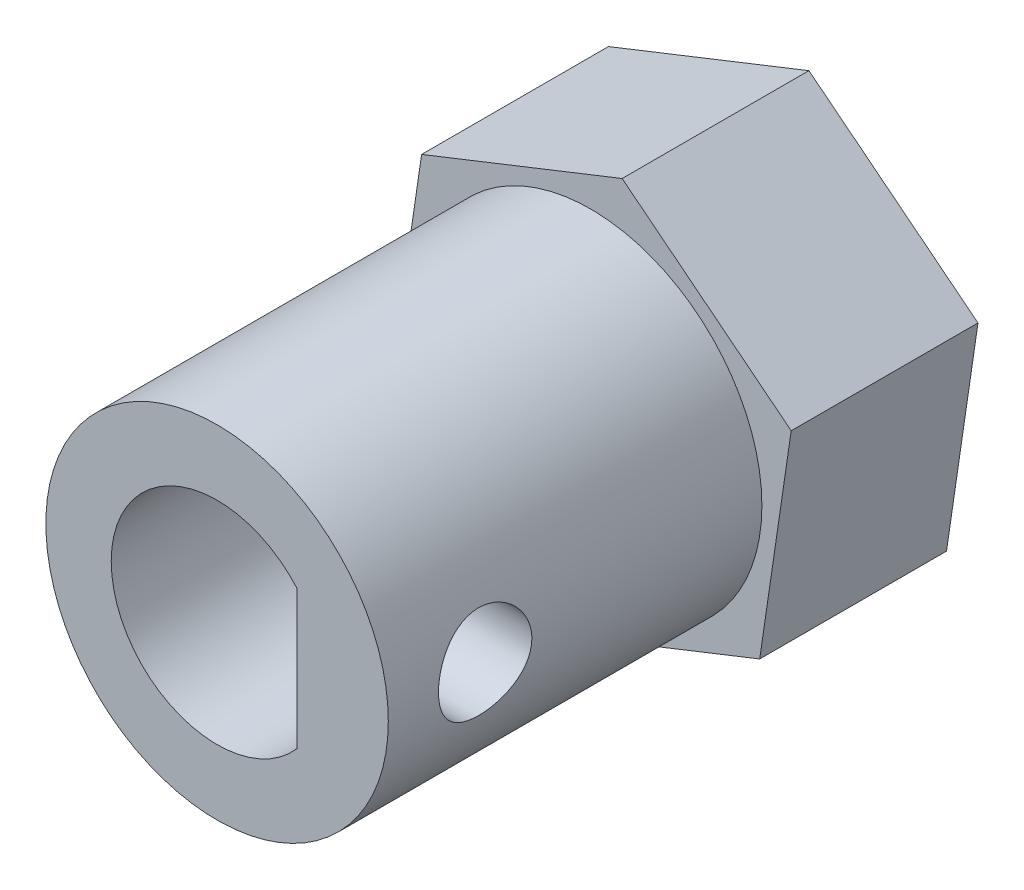
SolidWorks part; units mm, degrees
ref_plane "前视基准面" through (0, 0, 0) normal (0, 0, 1) x (1, 0, 0)
ref_plane "上视基准面" through (0, 0, 0) normal (0, 1, 0) x (1, 0, 0)
ref_plane "右视基准面" through (0, 0, 0) normal (1, 0, 0) x (0, 0, -1)
sketch "草图1" plane through (0, 0, 0) normal (0, 0, 1) x (1, 0, 0)
  line L1 (5.4299, -4.303) -> (6.4415, 2.551)
  line L2 (6.4415, 2.551) -> (1.0115, 6.854)
  line L3 (1.0115, 6.854) -> (-5.4299, 4.303)
  line L4 (-5.4299, 4.303) -> (-6.4415, -2.551)
  line L5 (-6.4415, -2.551) -> (-1.0115, -6.854)
  line L6 (-1.0115, -6.854) -> (5.4299, -4.303)
  circle A0 centre (0, 0) radius 6 construction
  dimension "D1" = 12
extrude "凸台-拉伸1" add sketch "草图1" along normal blind 6
sketch "草图2" plane through (0, 0, 6) normal (0, 0, 1) x (1, 0, 0)
  circle A0 centre (0, 0) radius 5.5
  dimension "D1" = 11
extrude "凸台-拉伸2" add sketch "草图2" along normal blind 12
sketch "草图3" plane through (0, 0, 0) normal (0, 0, -1) x (-1, 0, 0)
  circle A0 centre (0, 0) radius 1.6
  dimension "D1" = 3.2
extrude "切除-拉伸1" cut sketch "草图3" against normal blind 6
sketch "草图4" plane through (0, 0, 18) normal (0, 0, 1) x (1, 0, 0)
  line L0 (0, 0) -> (2.45, 0) construction
  line L1 (2.45, 1.7313) -> (2.45, -1.7313)
  arc A0 (2.45, 1.7313) -> (2.45, -1.7313) centre (0, 0) ccw
  dimension "D1" = 6
  dimension "D2" = 2.45
extrude "切除-拉伸2" cut sketch "草图4" against normal up to surface (12 mm away) up to face at (5.5, 0, 6)
sketch "草图5" plane through (2.45, 0, 0) normal (-1, 0, 0) x (0, 0, 1)
  circle A0 centre (14.888, 0) radius 1.5
  dimension "D1" = 3
extrude "切除-拉伸3" cut sketch "草图5" against normal blind 10
sketch "草图6" plane through (0, 0, 18) normal (0, 0, 1) x (1, 0, 0)
  line L0 (2.5691, 2.227) -> (2.5691, -2.227)
  arc A0 (2.5691, 2.227) -> (2.5691, -2.227) centre (0, 0) ccw
  dimension "D1" = 6.8
extrude "切除-拉伸4" cut sketch "草图6" against normal up to surface (12 mm away) up to face at (5.5, 0, 6)
